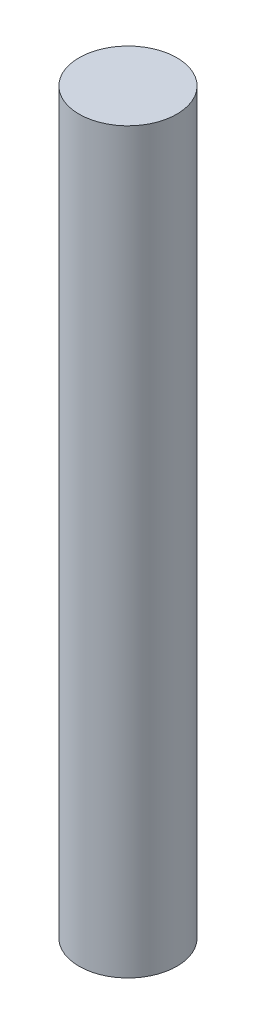
SolidWorks part; units mm, degrees
ref_plane "Front Plane" through (0, 0, 0) normal (0, 0, 1) x (1, 0, 0)
ref_plane "Top Plane" through (0, 0, 0) normal (0, 1, 0) x (1, 0, 0)
ref_plane "Right Plane" through (0, 0, 0) normal (1, 0, 0) x (0, 0, -1)
sketch "Sketch1" plane through (0, 0, 0) normal (0, 1, 0) x (1, 0, 0)
  circle A0 centre (-72.3175, 6.7875) radius 0.265
extrude "Boss-Extrude1" add sketch "Sketch1" along normal blind 4
